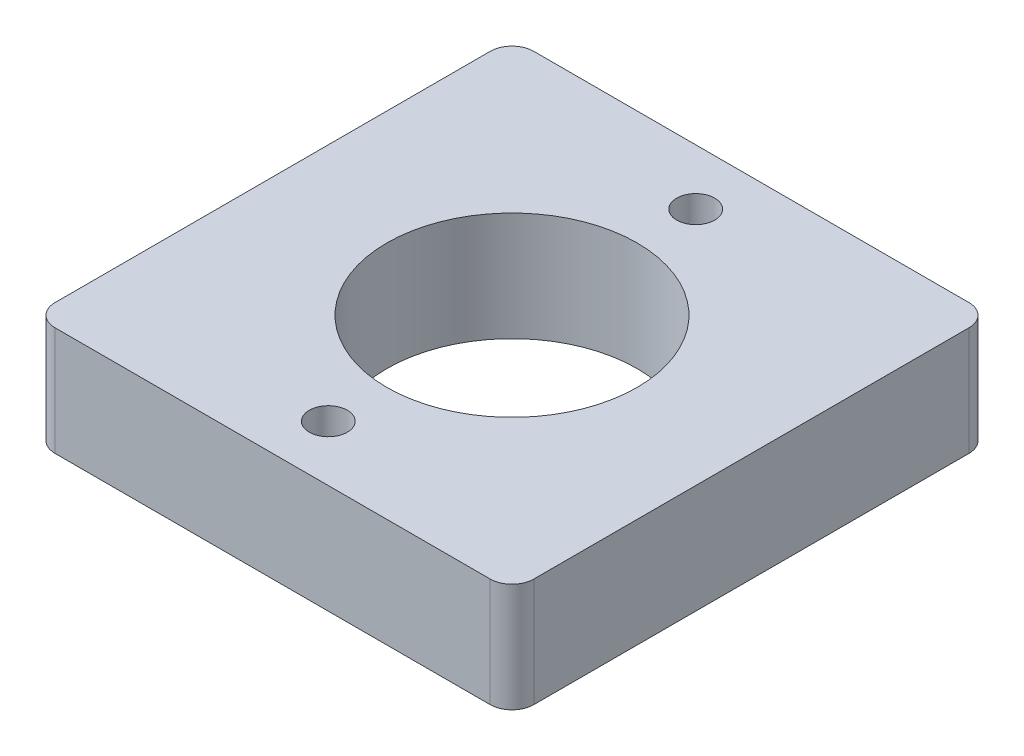
SolidWorks part; units mm, degrees
ref_plane "Alzado" through (0, 0, 0) normal (0, 0, 1) x (1, 0, 0)
ref_plane "Planta" through (0, 0, 0) normal (0, 1, 0) x (1, 0, 0)
ref_plane "Vista lateral" through (0, 0, 0) normal (1, 0, 0) x (0, 0, -1)
sketch "Croquis1" plane through (0, 0, 0) normal (0, 1, 0) x (1, 0, 0)
  line L1 (-22, -22) -> (22, -22)
  line L2 (-22, -22) -> (-22, 22)
  line L3 (-22, 22) -> (22, 22)
  line L4 (22, -22) -> (22, 22)
  line L5 (-22, -22) -> (22, 22) construction
  line L6 (-22, 22) -> (22, -22) construction
  circle A0 centre (0, 0) radius 11.5
  point P0 (0, 0)
  dimension "D3" = 23
  dimension "D1" = 44
  dimension "D2" = 44
extrude "Saliente-Extruir1" add sketch "Croquis1" along normal blind 10
sketch "Croquis2" plane through (0, 10, 0) normal (0, 1, 0) x (1, 0, 0)
  line L0 (-22, 22) -> (-22, -22) construction
  line L1 (22, -11.75) -> (-22, -11.75) construction
  line L2 (22, -11.75) -> (22, 11.75) construction
  line L3 (22, 11.75) -> (-22, 11.75) construction
  line L4 (-22, -11.75) -> (-22, 11.75) construction
  line L5 (22, -11.75) -> (-22, 11.75) construction
  line L6 (22, 11.75) -> (-22, -11.75) construction
  line L7 (-22, 16.88) -> (22, 16.88) construction
  line L8 (22, -22) -> (22, 22) construction
  line L9 (0, 22) -> (0, -22) construction
  line L10 (22, 22) -> (-22, 22) construction
  line L11 (-22, -22) -> (22, -22) construction
  line L12 (-22, -16.88) -> (22, -16.88) construction
  circle A0 centre (0, 16.88) radius 1.75
  circle A1 centre (0, -16.88) radius 1.75
  point P0 (0, 0)
  point P18 (0, 16.88)
  point P19 (0, -16.88)
  dimension "D4" = 3.5
  dimension "D5" = 3.5
  dimension "D1" = 23.5
  dimension "D2" = 5.13
  dimension "D3" = 5.13
extrude "Cortar-Extruir1" cut sketch "Croquis2" against normal through all
fillet "Redondeo1" radius 2 4 edges at (22, 5, -22) (22, 5, 22) (-22, 5, 22) (-22, 5, -22)
